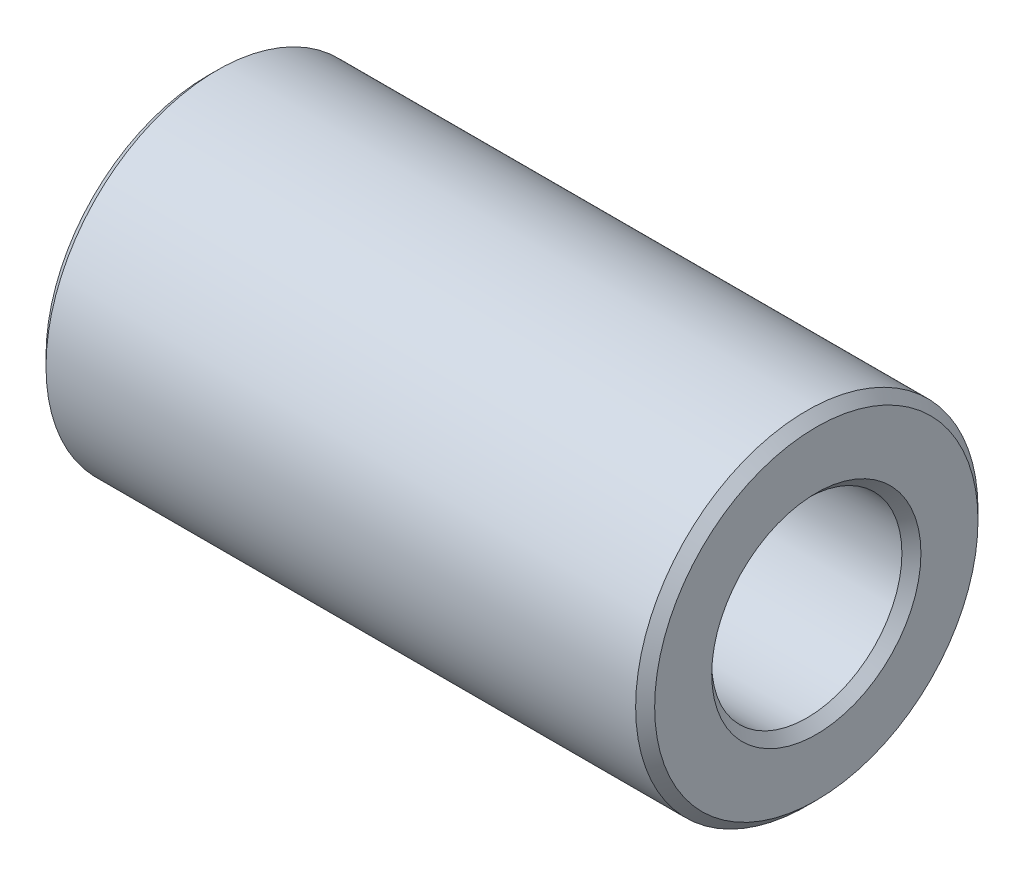
SolidWorks part; units mm, degrees
ref_plane "Plan1" through (0, 0, 0) normal (0, 0, 1) x (1, 0, 0)
ref_plane "Plan2" through (0, 0, 0) normal (0, 1, 0) x (1, 0, 0)
ref_plane "Plan3" through (0, 0, 0) normal (1, 0, 0) x (0, 0, -1)
sketch "Esquisse1" plane through (0, 0, 0) normal (0, 0, 1) x (1, 0, 0)
  line L0 (0, 0) -> (20, 0) construction
  line L1 (-16, 9) -> (16, 9)
  point P5 (0, 9)
  dimension "D1" = 9
  dimension "D2" = 32
revolve "Base-Révol.-Mince" add sketch "Esquisse1" angle 360 about L0
chamfer "Chanfrein1" distance 0.5 angle 45
